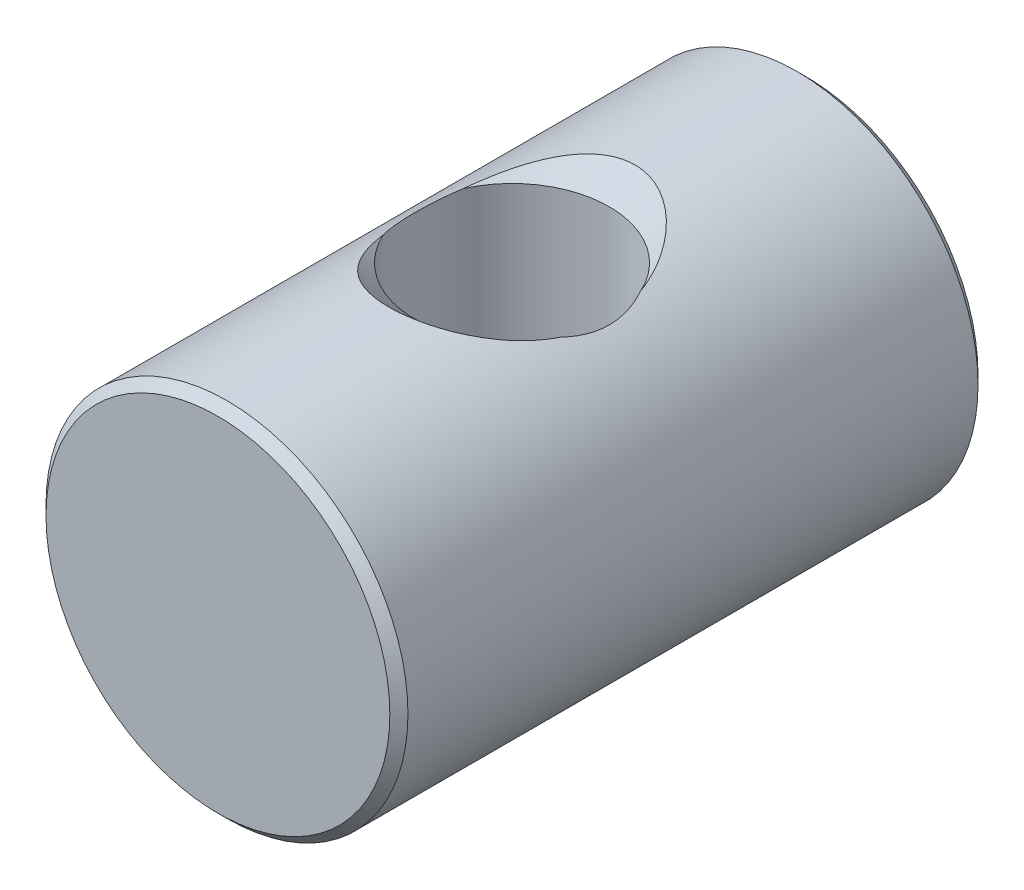
SolidWorks part; units mm, degrees
ref_plane "Alzado" through (0, 0, 0) normal (0, 0, 1) x (1, 0, 0)
ref_plane "Planta" through (0, 0, 0) normal (0, 1, 0) x (1, 0, 0)
ref_plane "Vista lateral" through (0, 0, 0) normal (1, 0, 0) x (0, 0, -1)
sketch "Croquis1" plane through (0, 0, 0) normal (0, 1, 0) x (1, 0, 0)
  line L0 (0, 6.5) -> (0, -25.5697) construction
  line L1 (0, 6.5) -> (4, 6.5)
  line L2 (4, 6.5) -> (4, -6.5)
  line L3 (4, -6.5) -> (0, -6.5)
  line L4 (0, 6.5) -> (0, -6.5)
  dimension "D1" = 8
  dimension "D2" = 13
  dimension "D3" = 6.5
revolve "Revolución1" add sketch "Croquis1" angle 360 about L0
chamfer "Chaflán1" distance 0.2 angle 45 2 edges at (-4, 0, -6.5) (-4, 0, 6.5)
sketch "Croquis2" plane through (0, 0, 0) normal (0, 1, 0) x (1, 0, 0)
  circle A0 centre (0, 0) radius 2.15
  dimension "D1" = 4.3
extrude "Cortar-Extruir1" cut sketch "Croquis2" against normal through all and the other way through all
sketch "Croquis3" plane through (0, 0, 0) normal (1, 0, 0) x (0, 0, -1)
  line L0 (0, 0) -> (0, 5.6553) construction
  line L1 (0, 2.8277) -> (-1.4176, 2.8277)
  line L2 (-1.4176, 2.8277) -> (-3.6183, 4.8076)
  line L3 (-3.6183, 4.8076) -> (0, 4.8076)
  line L4 (0, 4.8076) -> (0, 2.8277)
revolve "Cortar-Revolución1" cut sketch "Croquis3" angle 360 about L0
mirror "Simetría1" about plane through (0, 0, 0) normal (0, 1, 0) of "Cortar-Revolución1"
